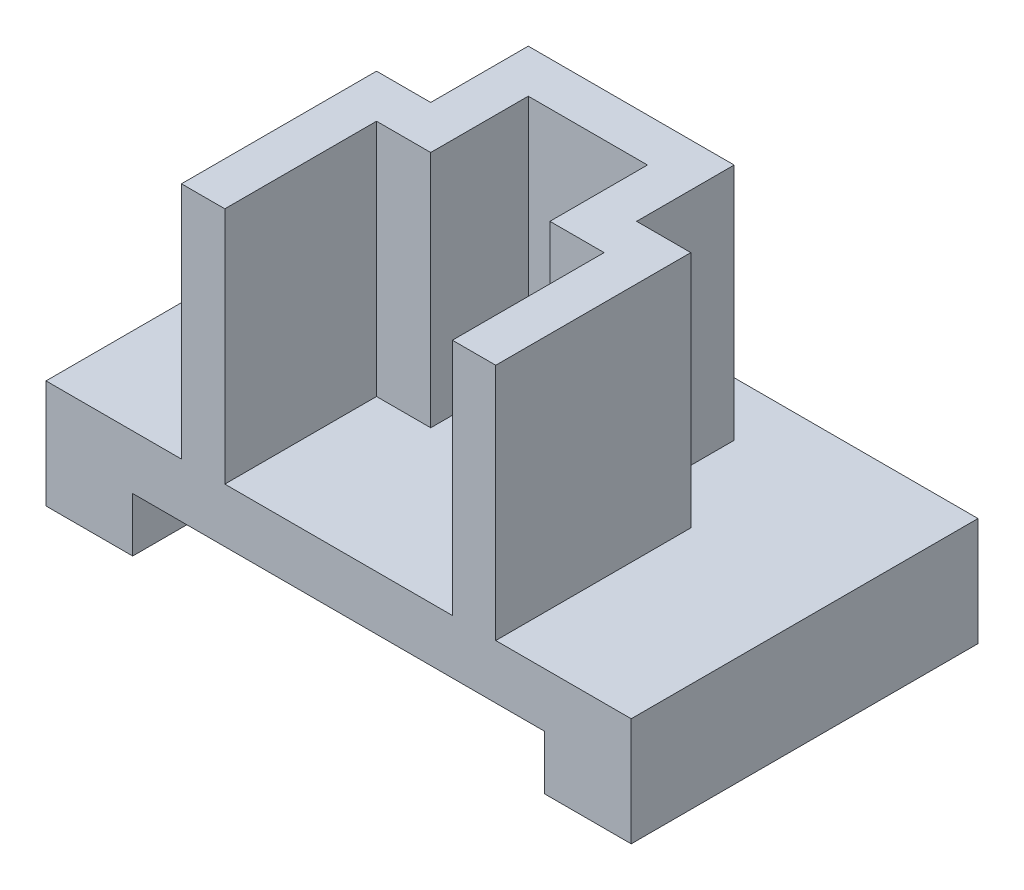
SolidWorks part; units mm, degrees
ref_plane "前视基准面" through (0, 0, 0) normal (0, 0, 1) x (1, 0, 0)
ref_plane "上视基准面" through (0, 0, 0) normal (0, 1, 0) x (1, 0, 0)
ref_plane "右视基准面" through (0, 0, 0) normal (1, 0, 0) x (0, 0, -1)
other "Configuration Table"
sketch "草图1" plane through (0, 0, 0) normal (0, 0, 1) x (1, 0, 0)
  line L0 (0, -209.4716) -> (0, 0) construction
  line L3 (-19, 0) -> (19, 0)
  line L4 (19, -5) -> (19, 0)
  line L5 (19, -5) -> (27, -5)
  line L7 (-27, 5) -> (27, 5)
  line L8 (27, -5) -> (27, 5)
  line L9 (0, 5) -> (0, 10251.4028) construction
  line L10 (-27, -5) -> (-27, 5)
  line L11 (-19, -5) -> (-27, -5)
  line L12 (-19, -5) -> (-19, 0)
  dimension "D1" = 54
  dimension "D2" = 38
  dimension "D3" = 10
  dimension "D4" = 5
extrude "凸台-拉伸1" add sketch "草图1" along normal blind 32
sketch "草图2" plane through (0, 5, 0) normal (0, 1, 0) x (1, 0, 0)
  line L0 (0, -1000) -> (0, -9) construction
  line L2 (27, -32) -> (-27, -32) construction
  line L3 (-14.5, -32) -> (-10.5, -32)
  line L4 (-14.5, -32) -> (-14.5, -14)
  line L5 (-14.5, -14) -> (-9.5, -14)
  line L6 (-10.5, -32) -> (-10.5, -18)
  line L7 (0, -5) -> (0, 49000) construction
  line L8 (-10.5, -18) -> (-5.5, -18)
  line L9 (-9.5, -14) -> (-9.5, -5)
  line L11 (-5.5, -18) -> (-5.5, -9)
  line L14 (-5.5, -9) -> (5.5, -9)
  line L16 (-9.5, -5) -> (9.5, -5)
  line L17 (5.5, -18) -> (5.5, -9)
  line L18 (9.5, -14) -> (9.5, -5)
  line L19 (10.5, -18) -> (5.5, -18)
  line L20 (10.5, -32) -> (10.5, -18)
  line L21 (14.5, -14) -> (9.5, -14)
  line L22 (14.5, -32) -> (14.5, -14)
  line L23 (14.5, -32) -> (10.5, -32)
  dimension "D1" = 19
  dimension "D2" = 4
  dimension "D3" = 18
  dimension "D4" = 27
  dimension "D5" = 11
  dimension "D6" = 21
  dimension "D7" = 29
  dimension "D8" = 4
extrude "凸台-拉伸2" add sketch "草图2" along normal blind 22
